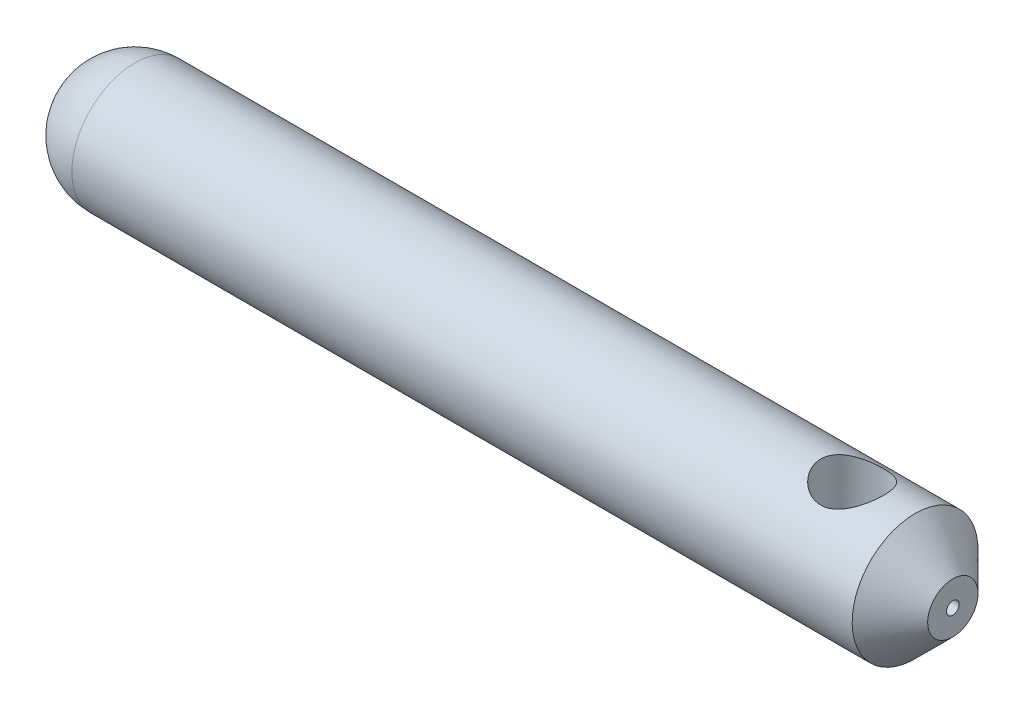
SolidWorks part; units mm, degrees
ref_plane "Front Plane" through (0, 0, 0) normal (0, 0, 1) x (1, 0, 0)
ref_plane "Top Plane" through (0, 0, 0) normal (0, 1, 0) x (1, 0, 0)
ref_plane "Right Plane" through (0, 0, 0) normal (1, 0, 0) x (0, 0, -1)
sketch "Sketch3" plane through (0, 0, 0) normal (0, 0, 1) x (1, 0, 0)
  line L0 (-1.904, 4.6112) -> (60.096, 4.6112)
  line L1 (60.096, 4.6112) -> (63.096, 1.6112)
  line L2 (63.096, 1.6112) -> (63.096, -0.3888)
  line L3 (63.096, -0.3888) -> (-6.904, -0.3888)
  arc A0 (-6.904, -0.3888) -> (-1.904, 4.6112) centre (-1.904, -0.3888) cw
  dimension "D1" = 5
  dimension "D2" = 45
  dimension "D3" = 70
  dimension "D4" = 2
revolve "Revolve1" add sketch "Sketch3" angle 360 about L3
sketch "Sketch4" plane through (63.096, 0, 0) normal (1, 0, 0) x (0, 0, -1)
  circle A0 centre (0, -0.3888) radius 0.5
  circle A1 centre (0, -0.3888) radius 2 construction
  dimension "D1" = 1
extrude "Cut-Extrude1" cut sketch "Sketch4" against normal blind 60
ref_plane "Plane1" through (0, 4.6112, 0) normal (0, 1, 0) x (1, 0, 0)
sketch "Sketch5" plane through (0, 4.6112, 0) normal (0, 1, 0) x (1, 0, 0)
  line L0 (60.096, -5) -> (60.096, 5) construction
  circle A0 centre (55.096, 0) radius 2.5
  dimension "D1" = 5
  dimension "D2" = 5
extrude "Cut-Extrude2" cut sketch "Sketch5" against normal through all both and the other way through all
